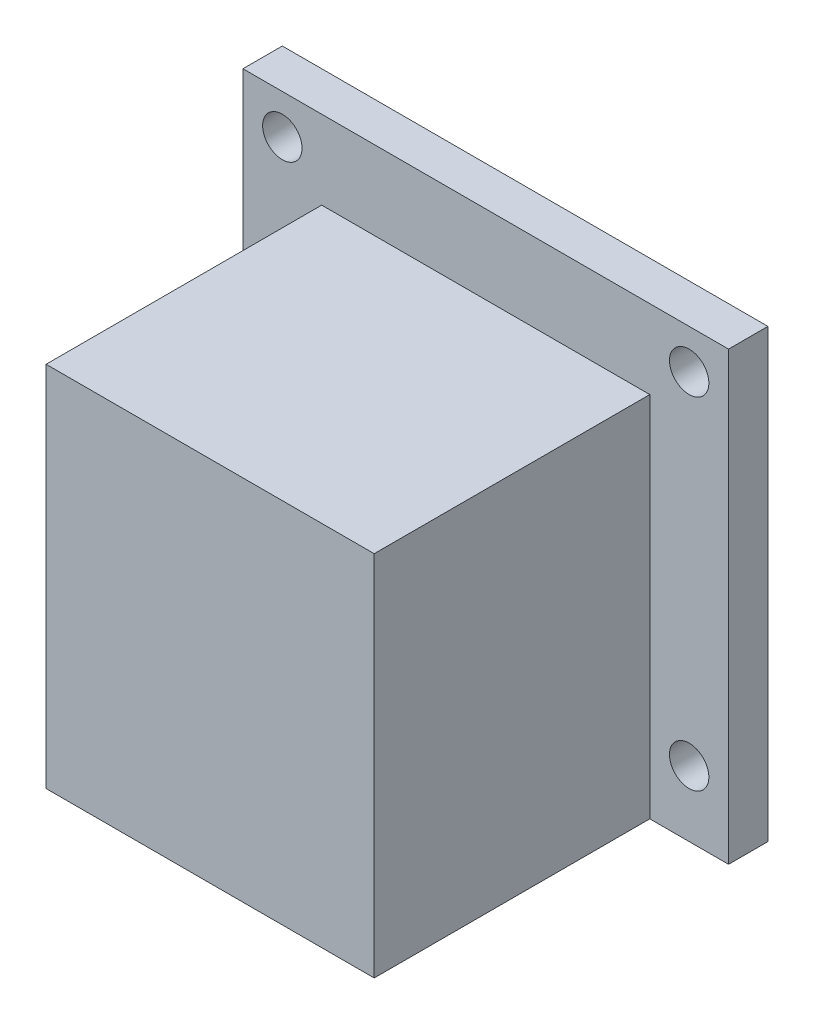
SolidWorks part; units mm, degrees
ref_plane "前视基准面" through (0, 0, 0) normal (0, 0, 1) x (1, 0, 0)
ref_plane "上视基准面" through (0, 0, 0) normal (0, 1, 0) x (1, 0, 0)
ref_plane "右视基准面" through (0, 0, 0) normal (1, 0, 0) x (0, 0, -1)
sketch "草图1" plane through (0, 0, 0) normal (0, 1, 0) x (1, 0, 0)
  line L1 (12.5, -12.5) -> (-12.5, -12.5)
  line L2 (12.5, -12.5) -> (12.5, 12.5)
  line L3 (12.5, 12.5) -> (-12.5, 12.5)
  line L4 (-12.5, -12.5) -> (-12.5, 12.5)
  line L5 (12.5, -12.5) -> (-12.5, 12.5) construction
  line L6 (12.5, 12.5) -> (-12.5, -12.5) construction
  point P0 (0, 0)
  dimension "D1" = 25
  dimension "D2" = 25
extrude "凸台-拉伸1" add sketch "草图1" along normal blind 25
shell "抽壳2" thickness 2
sketch "草图2" plane through (0, 2, 0) normal (0, 1, 0) x (1, 0, 0)
  line L4 (-10.5, 12.5) -> (-10.5, -10.5)
  line L5 (-10.5, -10.5) -> (10.5, -10.5)
  line L6 (10.5, -10.5) -> (10.5, 12.5)
  line L7 (10.5, 12.5) -> (-10.5, 12.5)
  line L8 (-10.5, 12.5) -> (-10.5, -10.5)
  line L9 (-10.5, -10.5) -> (10.5, -10.5)
  line L10 (10.5, -10.5) -> (10.5, 12.5)
  line L11 (10.5, 12.5) -> (-10.5, 12.5)
  dimension "D1" = 0
extrude "切除-拉伸1" cut sketch "草图2" against normal blind 25
sketch "草图3" plane through (0, 25, 0) normal (0, 1, 0) x (1, 0, 0)
  line L4 (-12.5, 12.5) -> (-12.5, -12.5)
  line L5 (-12.5, -12.5) -> (12.5, -12.5)
  line L6 (12.5, -12.5) -> (12.5, 12.5)
  line L7 (12.5, 12.5) -> (-12.5, 12.5)
  line L8 (-12.5, 12.5) -> (-12.5, -12.5)
  line L9 (-12.5, -12.5) -> (12.5, -12.5)
  line L10 (12.5, -12.5) -> (12.5, 12.5)
  line L11 (12.5, 12.5) -> (-12.5, 12.5)
  dimension "D1" = 0
extrude "凸台-拉伸2" add sketch "草图3" along normal blind 3
sketch "草图5" plane through (0, 0, -12.5) normal (0, 0, -1) x (-1, 0, 0)
  line L0 (18.5, 0) -> (18.5, 34)
  line L1 (18.5, 34) -> (-18.5, 34)
  line L2 (-18.5, 34) -> (-18.5, 0)
  line L3 (-18.5, 0) -> (-12.5, 0)
  line L4 (12.5, 0) -> (18.5, 0)
  line L8 (-12.5, 0) -> (-10.5, 0)
  line L9 (-10.5, 0) -> (-10.5, 23)
  line L10 (-10.5, 23) -> (10.5, 23)
  line L11 (10.5, 23) -> (10.5, 0)
  line L12 (10.5, 0) -> (12.5, 0)
  line L13 (12.5, 0) -> (12.5, 28)
  line L14 (12.5, 28) -> (-12.5, 28)
  line L15 (-12.5, 28) -> (-12.5, 0)
  line L21 (12.5, 0) -> (12.5, 28)
  line L22 (12.5, 28) -> (-12.5, 28)
  line L23 (-12.5, 28) -> (-12.5, 0)
  dimension "D1" = 0
  dimension "D2" = 6
extrude "凸台-拉伸3" add sketch "草图5" against normal blind 4
sketch "草图6" plane through (0, 0, -12.5) normal (0, 0, -1) x (-1, 0, 0)
  line L8 (10.5, 0) -> (18.5, 0)
  line L9 (18.5, 0) -> (18.5, 34)
  line L10 (18.5, 34) -> (-18.5, 34)
  line L11 (-18.5, 34) -> (-18.5, 0)
  line L12 (-18.5, 0) -> (-10.5, 0)
  line L13 (-10.5, 0) -> (-10.5, 23)
  line L14 (-10.5, 23) -> (10.5, 23)
  line L15 (10.5, 23) -> (10.5, 0)
  line L16 (10.5, 0) -> (18.5, 0)
  line L17 (18.5, 0) -> (18.5, 34)
  line L18 (18.5, 34) -> (-18.5, 34)
  line L19 (-18.5, 34) -> (-18.5, 0)
  line L20 (-18.5, 0) -> (-10.5, 0)
  line L21 (-10.5, 0) -> (-10.5, 23)
  line L22 (-10.5, 23) -> (10.5, 23)
  line L23 (10.5, 23) -> (10.5, 0)
  dimension "D1" = 0
extrude "切除-拉伸2" cut sketch "草图6" against normal blind 1
sketch "草图7" plane through (0, 0, -11.5) normal (0, 0, -1) x (-1, 0, 0)
  line L0 (-18.5, 34) -> (-18.5, 0) construction
  line L1 (-18.5, 0) -> (-10.5, 0) construction
  line L2 (18.5, 34) -> (-18.5, 34) construction
  line L3 (0, -1000) -> (0, 49000) construction
  circle A0 centre (-15.5, 5) radius 1.5
  circle A1 centre (-15.5, 31) radius 1.5
  circle A2 centre (15.5, 5) radius 1.5
  circle A3 centre (15.5, 31) radius 1.5
  dimension "D1" = 3
  dimension "D6" = 3
  dimension "D2" = 3
  dimension "D3" = 5
  dimension "D4" = 3
  dimension "D5" = 3
extrude "切除-拉伸3" cut sketch "草图7" against normal through all
